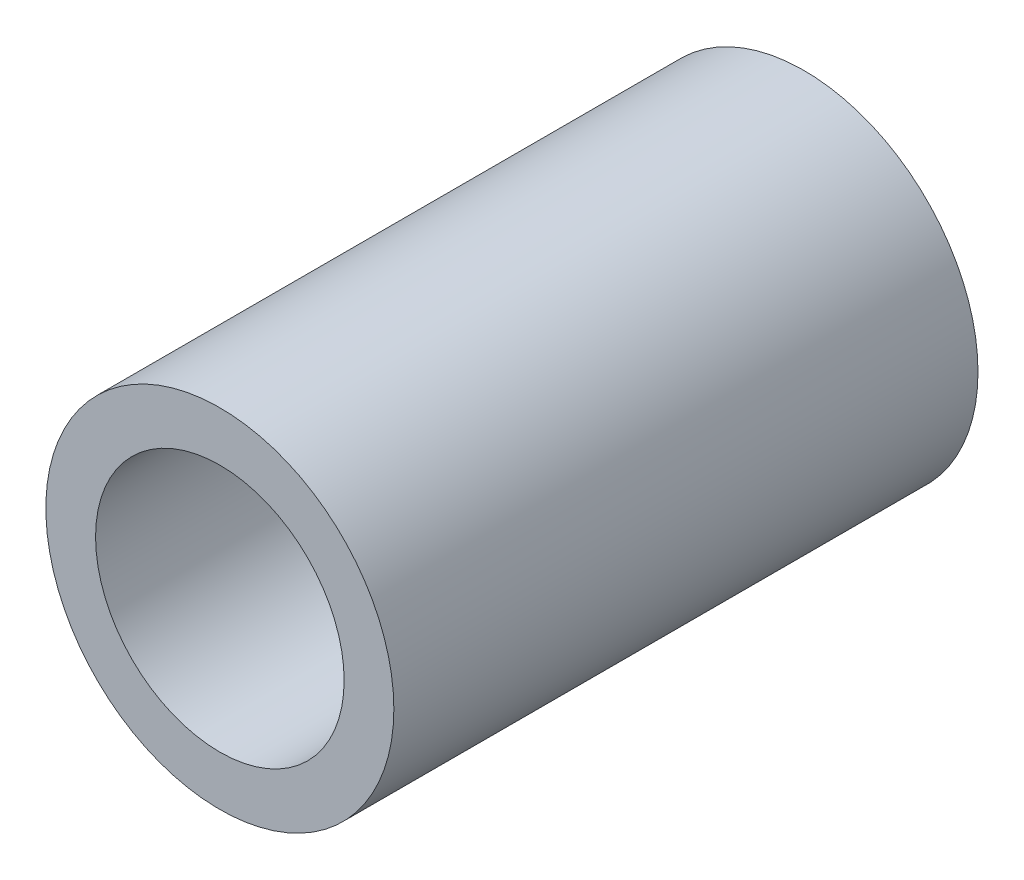
SolidWorks part; units mm, degrees
ref_plane "前视基准面" through (0, 0, 0) normal (0, 0, 1) x (1, 0, 0)
ref_plane "上视基准面" through (0, 0, 0) normal (0, 1, 0) x (1, 0, 0)
ref_plane "右视基准面" through (0, 0, 0) normal (1, 0, 0) x (0, 0, -1)
sketch "草图1" plane through (0, 0, 0) normal (0, 0, 1) x (1, 0, 0)
  circle A0 centre (0, 0) radius 5
  circle A1 centre (0, 0) radius 7
  dimension "D1" = 2
extrude "凸台-拉伸1" add sketch "草图1" along normal blind 23.5
